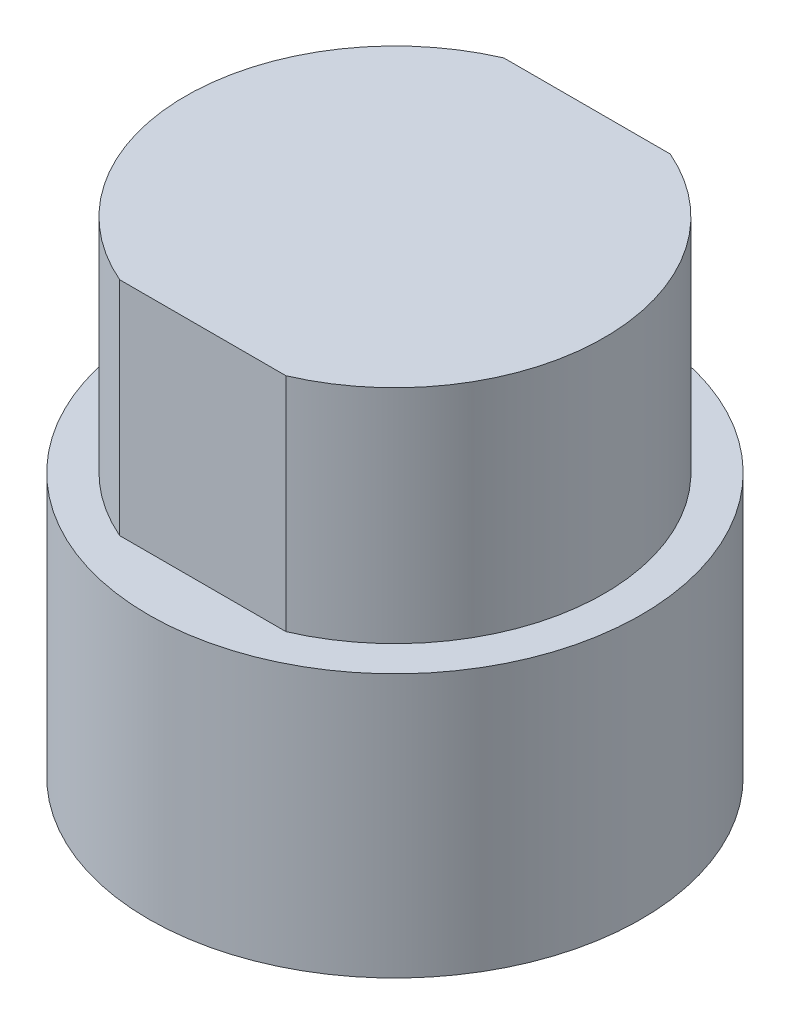
SolidWorks part; units mm, degrees
ref_plane "Front Plane" through (0, 0, 0) normal (0, 0, 1) x (1, 0, 0)
ref_plane "Top Plane" through (0, 0, 0) normal (0, 1, 0) x (1, 0, 0)
ref_plane "Right Plane" through (0, 0, 0) normal (1, 0, 0) x (0, 0, -1)
sketch "Sketch1" plane through (0, 0, 0) normal (0, 1, 0) x (1, 0, 0)
  circle A0 centre (0, 0) radius 10
  dimension "D1" = 20
extrude "Boss-Extrude1" add sketch "Sketch1" along normal blind 10.7
sketch "Sketch2" plane through (0, 10.7, 0) normal (0, 1, 0) x (1, 0, 0)
  line L0 (-3.3779, -7.8) -> (3.3779, -7.8)
  line L1 (3.3779, -7.8) -> (3.3779, 7.8) construction
  line L2 (3.3779, 7.8) -> (-3.3779, 7.8)
  circle A0 centre (0, 0) radius 8.5
  circle M1 centre (0, 0) radius 10
  dimension "D1" = 17
  dimension "D2" = 15.6
extrude "Boss-Extrude2" add sketch "Sketch2" along normal blind 9 contours L0 L1 L2 M1 | L1 M1
